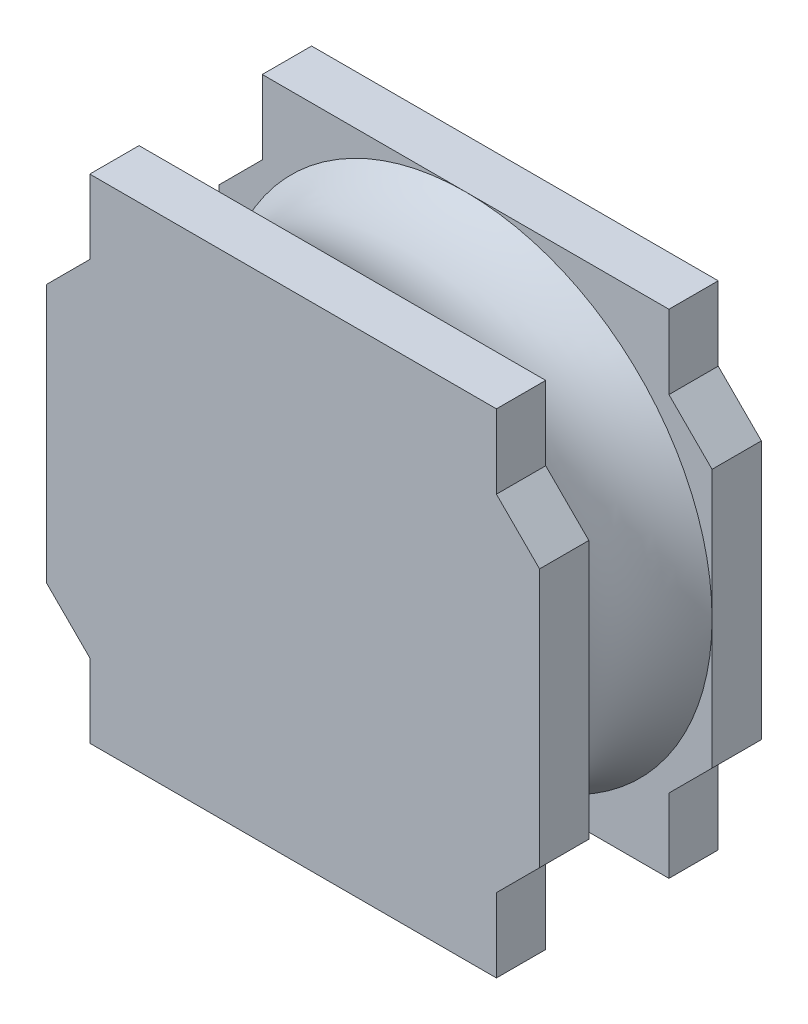
SolidWorks part; units mm, degrees
ref_plane "Front Plane" through (0, 0, 0) normal (0, 0, 1) x (1, 0, 0)
ref_plane "Top Plane" through (0, 0, 0) normal (0, 1, 0) x (1, 0, 0)
ref_plane "Right Plane" through (0, 0, 0) normal (1, 0, 0) x (0, 0, -1)
sketch "Sketch1" plane through (0, 0, 0) normal (0, 0, 1) x (1, 0, 0)
  line L0 (0, 0) -> (0, 2) construction
  line L1 (0, 0) -> (2, 0) construction
  line L2 (-1.65, 2) -> (1.65, 2)
  line L3 (1.65, 2) -> (1.65, 1.4)
  line L4 (1.65, 1.4) -> (2, 1.05)
  line L5 (2, 1.05) -> (2, -1.05)
  line L6 (-2, 1.05) -> (-2, -1.05)
  line L7 (-1.65, 1.4) -> (-2, 1.05)
  line L8 (-1.65, 2) -> (-1.65, 1.4)
  line L9 (1.65, -1.4) -> (2, -1.05)
  line L10 (1.65, -2) -> (1.65, -1.4)
  line L11 (-1.65, -2) -> (1.65, -2)
  line L12 (-1.65, -2) -> (-1.65, -1.4)
  line L13 (-1.65, -1.4) -> (-2, -1.05)
  point P17 (-2, 0)
  dimension "D1" = 4
  dimension "D2" = 4
  dimension "D3" = 2.1
  dimension "D4" = 45
  dimension "D5" = 3.3
extrude "Boss-Extrude1" add sketch "Sketch1" along normal blind 1.8
sketch "Sketch2" plane through (0, 0, 0) normal (0, 1, 0) x (1, 0, 0)
  line L0 (0, -0.4) -> (2, -0.4) construction
  line L1 (0, -0.4) -> (0, -1.4) construction
  line L2 (0, -1.4) -> (2, -1.4) construction
  line L3 (1.65, 0) -> (-1.65, 0) construction
  line L4 (1.65, -1.8) -> (-1.65, -1.8) construction
  line L5 (2, -0.4) -> (2, -1.4) construction
  line L6 (2, -0.9) -> (1.85, -0.9) construction
  line L7 (2, -0.4) -> (3.5, -0.4)
  line L8 (3.5, -0.4) -> (3.5, -1.4)
  line L9 (3.5, -1.4) -> (2, -1.4)
  spline S0 degree 2 poles (2, -0.4) (1.7, -0.9) (2, -1.4) knots 0 0 0 1 1 1
  point P10 (1.9136, -1.4)
  dimension "D1" = 0.4
  dimension "D2" = 0.4
  dimension "D3" = 0.15
  dimension "D4" = 1.5
  dimension "D5" = 2
revolve "Cut-Revolve1" cut sketch "Sketch2" angle 360 about L1
